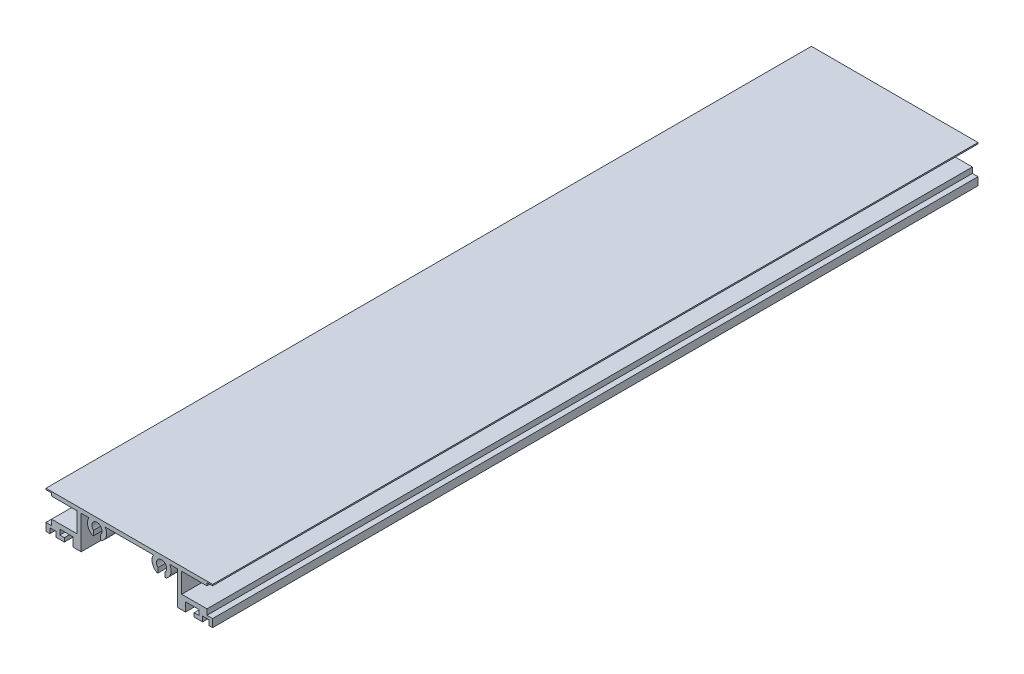
SolidWorks part; units mm, degrees
ref_plane "Piano frontale" through (0, 0, 0) normal (0, 0, 1) x (1, 0, 0)
ref_plane "Piano superiore" through (0, 0, 0) normal (0, 1, 0) x (1, 0, 0)
ref_plane "Piano destro" through (0, 0, 0) normal (1, 0, 0) x (0, 0, -1)
sketch "Schizzo1" plane through (0, 0, 0) normal (0, 0, 1) x (1, 0, 0)
  line L0 (-32.65, 14) -> (-32.65, 8.9)
  line L5 (-32.65, 14) -> (-30.15, 14)
  line L6 (-30.15, 14) -> (-30.15, 10.5)
  line L7 (-32.65, 8.9) -> (-30.45, 8.9)
  line L8 (-30.45, 8.9) -> (-30.45, 7.8)
  line L9 (-30.45, 7.8) -> (-20.55, 7.8)
  line L10 (-20.55, 7.8) -> (-20.55, 0)
  line L11 (-20.55, 0) -> (-30.45, 0)
  line L12 (-30.45, 0) -> (-30.45, -2.2)
  line L13 (-30.45, -2.2) -> (-32.65, -2.2)
  line L14 (-32.65, -2.2) -> (-32.65, -5.3)
  line L15 (-32.65, -5.3) -> (-31.15, -5.3)
  line L16 (-31.15, -5.3) -> (-31.15, -3.3)
  line L17 (-31.15, -3.3) -> (-28.75, -3.3)
  line L18 (-28.75, -3.3) -> (-28.75, -5.3)
  line L19 (-28.75, -5.3) -> (-25.45, -5.3)
  line L20 (-25.45, -5.3) -> (-25.45, -3.8)
  line L21 (-25.45, -3.8) -> (-27.25, -3.8)
  line L22 (-27.25, -3.8) -> (-27.25, -1.8)
  line L23 (-27.25, -1.8) -> (-22.05, -1.8)
  line L24 (-22.05, -1.8) -> (-22.05, -5.3)
  line L25 (-22.05, -5.3) -> (-18.85, -5.3)
  line L26 (-18.85, -5.3) -> (-18.85, 7.8)
  line L27 (-18.85, 7.8) -> (-15.8215, 7.8)
  line L28 (0, 9.4) -> (0, -9.65)
  line L29 (-30.15, 10.5) -> (-29.15, 10.5)
  line L30 (-29.15, 10.5) -> (-29.15, 9.4)
  line L31 (-29.15, 9.4) -> (29.15, 9.4)
  line L32 (11.4, 6.05) -> (-11.4, 6.05) construction
  line L33 (-12.6595, 3.681) -> (-12.5509, 3.8081) construction
  line L35 (-14.0741, 4.4052) -> (-14.0741, 2.5)
  line L37 (-11.2211, 4.4052) -> (-11.2211, 2.5)
  line L38 (-12.7442, 3.8081) -> (-12.6595, 3.681) construction
  line L39 (-14.4234, 2.5) -> (-14.0741, 2.5)
  line L40 (-11.2211, 2.5) -> (-10.8718, 2.5)
  line L41 (-9.4736, 7.8) -> (9.4736, 7.8)
  line L42 (12.7442, 3.8081) -> (12.6595, 3.681) construction
  line L43 (12.6595, 3.681) -> (12.5509, 3.8081) construction
  line L44 (11.2211, 2.5) -> (10.8718, 2.5)
  line L45 (14.4234, 2.5) -> (14.0741, 2.5)
  line L46 (11.2211, 4.4052) -> (11.2211, 2.5)
  line L47 (14.0741, 4.4052) -> (14.0741, 2.5)
  line L48 (29.15, 10.5) -> (29.15, 9.4)
  line L49 (30.15, 10.5) -> (29.15, 10.5)
  line L50 (18.85, 7.8) -> (15.8215, 7.8)
  line L51 (18.85, -5.3) -> (18.85, 7.8)
  line L52 (22.05, -5.3) -> (18.85, -5.3)
  line L53 (22.05, -1.8) -> (22.05, -5.3)
  line L54 (27.25, -1.8) -> (22.05, -1.8)
  line L55 (27.25, -3.8) -> (27.25, -1.8)
  line L56 (25.45, -3.8) -> (27.25, -3.8)
  line L57 (25.45, -5.3) -> (25.45, -3.8)
  line L58 (28.75, -5.3) -> (25.45, -5.3)
  line L59 (28.75, -3.3) -> (28.75, -5.3)
  line L60 (31.15, -3.3) -> (28.75, -3.3)
  line L61 (31.15, -5.3) -> (31.15, -3.3)
  line L62 (32.65, -5.3) -> (31.15, -5.3)
  line L63 (32.65, -2.2) -> (32.65, -5.3)
  line L64 (30.45, -2.2) -> (32.65, -2.2)
  line L65 (30.45, 0) -> (30.45, -2.2)
  line L66 (20.55, 0) -> (30.45, 0)
  line L67 (20.55, 7.8) -> (20.55, 0)
  line L68 (30.45, 7.8) -> (20.55, 7.8)
  line L69 (30.45, 8.9) -> (30.45, 7.8)
  line L70 (32.65, 8.9) -> (30.45, 8.9)
  line L71 (30.15, 14) -> (30.15, 10.5)
  line L72 (32.65, 14) -> (30.15, 14)
  line L73 (32.65, 14) -> (32.65, 8.9)
  arc A0 (-12.7442, 3.8081) -> (-12.5509, 3.8081) centre (-12.6476, 5.8029) ccw
  arc A1 (-15.8215, 7.8) -> (-14.4234, 2.5) centre (-12.6476, 5.8029) ccw
  arc A2 (-10.8718, 2.5) -> (-9.4736, 7.8) centre (-12.6476, 5.8029) ccw
  arc A3 (-11.2211, 4.4052) -> (-14.0741, 4.4052) centre (-12.6476, 5.8029) ccw
  arc A4 (11.2211, 4.4052) -> (14.0741, 4.4052) centre (12.6476, 5.8029) cw
  arc A5 (10.8718, 2.5) -> (9.4736, 7.8) centre (12.6476, 5.8029) cw
  arc A6 (15.8215, 7.8) -> (14.4234, 2.5) centre (12.6476, 5.8029) cw
  arc A7 (12.7442, 3.8081) -> (12.5509, 3.8081) centre (12.6476, 5.8029) cw
  point P0 (0, 0)
  point P6 (-20.45, -5.3)
  point P36 (-12.6595, 3.681)
  point P51 (0, 6.05)
  point P58 (0, 7.8)
  point P86 (12.6595, 3.681)
  dimension "D26" = 7.5
  dimension "D1" = 3.2
  dimension "D2" = 19.3
  dimension "D3" = 13.1
  dimension "D4" = 32.65
  dimension "D5" = 3.4
  dimension "D6" = 3.3
  dimension "D7" = 2.4
  dimension "D8" = 1.5
  dimension "D9" = 2
  dimension "D10" = 5.2
  dimension "D11" = 1.5
  dimension "D12" = 3.5
  dimension "D13" = 19.3
  dimension "D14" = 1.8
  dimension "D15" = 3.1
  dimension "D16" = 2.2
  dimension "D17" = 1.7
  dimension "D18" = 5.1
  dimension "D19" = 13.1
  dimension "D20" = 1.6
  dimension "D21" = 2.5
  dimension "D22" = 3.5
  dimension "D23" = 3.5
  dimension "D24" = 12.65
  dimension "D25" = 1.75
  dimension "D27" = 5.3
extrude "Estrusione-Estrusione1" add sketch "Schizzo1" along normal blind 300 contours A3 L37 L40 A2 L41 L28 L31 L30 L29 L6 L5 L0 L7 L8 L9 L10 L11 L12 L13 L14 L15 L16 L17 L18 L19 L20 L21 L22 L23 L24 L25 L26 L27 A1 L39 L35 | A6 L50 L51 L52 L53 L54 L55 L56 L57 L58 L59 L60 L61 L62 L63 L64 L65 L66 L67 L68 L69 L70 L73 L72 L71 L49 L48 L31 L28 L41 A5 L44 L46 A4 L47 L45
sketch "Schizzo2" plane through (0, 0, 300) normal (0, 0, 1) x (1, 0, 0)
  line L0 (29.15, 9.4) -> (32.65, 9.4)
  line L1 (32.65, 14) -> (32.65, 8.9) construction
  line L2 (32.65, 9.4) -> (32.65, 14)
  line L3 (32.65, 14) -> (29.15, 14)
  line L4 (29.15, 14) -> (29.15, 9.4)
extrude "Taglio-Estrusione1" cut sketch "Schizzo2" against normal through all
mirror "Specchia1" about plane through (0, 0, 0) normal (1, 0, 0) of "Taglio-Estrusione1"
